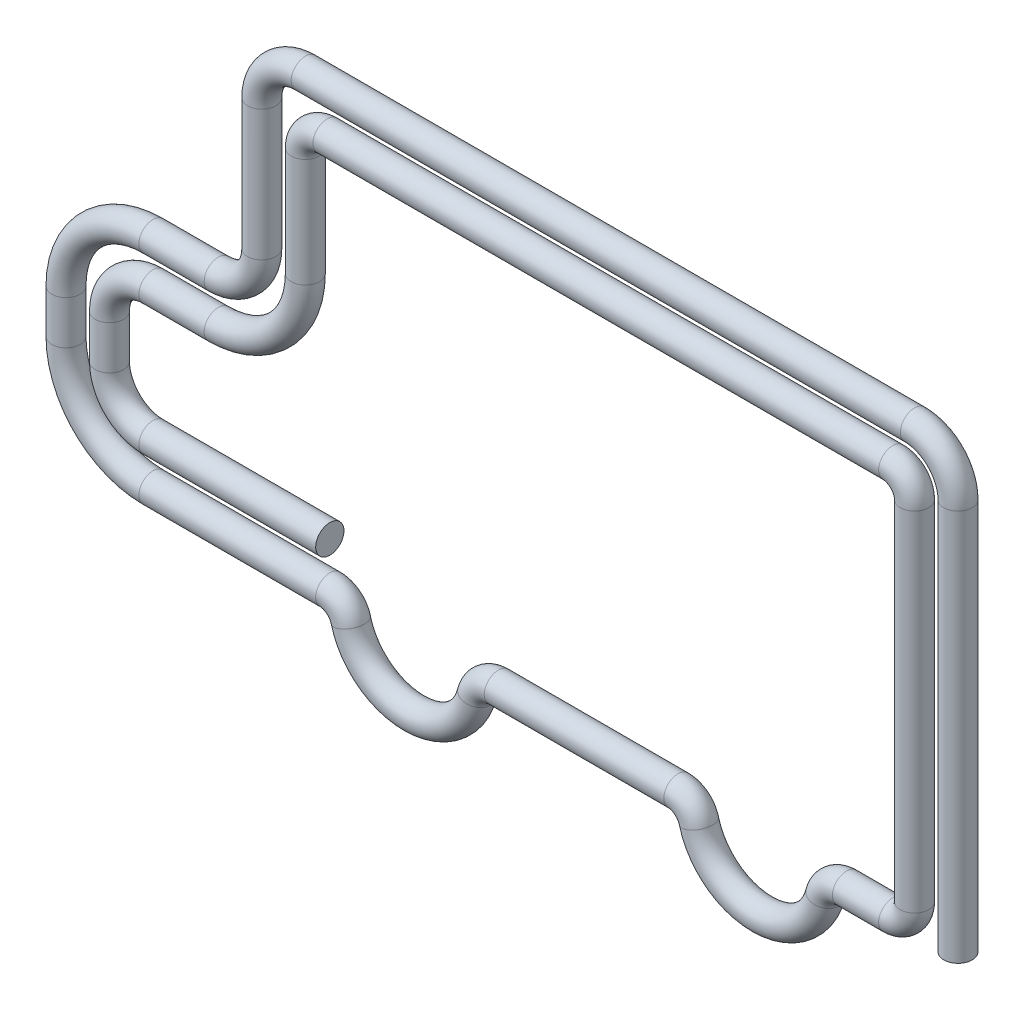
SolidWorks part; units mm, degrees
ref_plane "Спереди" through (0, 0, 0) normal (0, 0, 1) x (1, 0, 0)
ref_plane "Сверху" through (0, 0, 0) normal (0, 1, 0) x (1, 0, 0)
ref_plane "Справа" through (0, 0, 0) normal (1, 0, 0) x (0, 0, -1)
sketch "Эскиз1" plane through (0, 0, 0) normal (0, 0, 1) x (1, 0, 0)
  line L0 (0, 0) -> (0, 10) construction
  line L1 (-15, -10) -> (15, -10) construction
  line L2 (-15, -10) -> (-15, 10) construction
  line L3 (-15, 10) -> (15, 10) construction
  line L4 (15, -10) -> (15, 10) construction
  line L5 (-15, -10) -> (15, 10) construction
  line L6 (-15, 10) -> (15, -10) construction
  line L7 (-15, 8) -> (15, 8) construction
  line L8 (-15, -10) -> (-24, -10) construction
  line L9 (-15, -10) -> (-15, 0) construction
  line L10 (-15, 0) -> (-24, 0) construction
  line L11 (-24, -10) -> (-24, 0) construction
  circle A0 centre (-8, -10) radius 3 construction
  circle A1 centre (8, -10) radius 3 construction
  point P0 (0, 0)
  dimension "D3" = 6
  dimension "D4" = 8
  dimension "D1" = 30
  dimension "D2" = 20
  dimension "D5" = 9
  dimension "D6" = 10
  dimension "D7" = 2
sketch "Эскиз2" plane through (0, 0, 0) normal (0, 0, 1) x (1, 0, 0)
  line L0 (15, 10) -> (-13, 10)
  line L1 (-15, 8) -> (-15, 2)
  line L2 (-15, -10) -> (-15, 10) construction
  line L3 (-17, 0) -> (-20, 0)
  line L4 (-24, -4) -> (-24, -6)
  line L5 (-20, -10) -> (-11.873, -10)
  line L6 (-15, -10) -> (15, -10) construction
  line L7 (-4.127, -10) -> (4.127, -10)
  line L8 (11.873, -10) -> (14, -10)
  line L9 (15, -9) -> (15, 7)
  line L10 (14, 8) -> (-12, 8)
  line L12 (-24, -10) -> (-24, 0) construction
  line L13 (-13, 7) -> (-13, 2)
  line L14 (17, 8) -> (17, -10)
  line L15 (-17, -2) -> (-20, -2)
  line L16 (-22, -4) -> (-22, -6)
  line L17 (-20, -8) -> (-11.873, -8)
  line L18 (-13, 8) -> (-13, 2) construction
  circle A0 centre (-8, -10) radius 3 construction
  arc A1 (-10.9047, -10.75) -> (-5.0953, -10.75) centre (-8, -10) ccw
  arc A2 (5.0953, -10.75) -> (10.9047, -10.75) centre (8, -10) ccw
  circle A3 centre (8, -10) radius 3 construction
  arc A4 (-20, 0) -> (-24, -4) centre (-20, -4) ccw
  arc A5 (-24, -6) -> (-20, -10) centre (-20, -6) ccw
  arc A6 (-13, 10) -> (-15, 8) centre (-13, 8) ccw
  arc A7 (-15, 2) -> (-17, 0) centre (-17, 2) cw
  arc A8 (15, 10) -> (17, 8) centre (15, 8) cw
  arc A9 (-11.873, -10) -> (-10.9047, -10.75) centre (-11.873, -11) cw
  arc A10 (-5.0953, -10.75) -> (-4.127, -10) centre (-4.127, -11) cw
  arc A11 (4.127, -10) -> (5.0953, -10.75) centre (4.127, -11) cw
  arc A12 (10.9047, -10.75) -> (11.873, -10) centre (11.873, -11) cw
  arc A13 (14, -10) -> (15, -9) centre (14, -9) ccw
  arc A14 (15, 7) -> (14, 8) centre (14, 7) ccw
  arc A15 (-13, 2) -> (-17, -2) centre (-17, 2) cw
  arc A16 (-20, -2) -> (-22, -4) centre (-20, -4) ccw
  arc A17 (-22, -6) -> (-20, -8) centre (-20, -6) ccw
  arc A18 (-13, 7) -> (-12, 8) centre (-12, 7) cw
  point P2 (0, 0)
  point P38 (-24, -10)
  point P41 (-15, 10)
  point P44 (-15, 0)
  point P48 (-11, -10)
  point P51 (-5, -10)
  point P54 (5, -10)
  point P57 (11, -10)
  point P60 (15, -10)
  point P63 (15, 8)
  point P75 (0, 0)
  dimension "D3" = 4
  dimension "D4" = 2
  dimension "D5" = 2
  dimension "D6" = 1
  dimension "D2" = 1
  dimension "D1" = 2
  dimension "D7" = 2
ref_plane "Плоскость1" through (17, -10, 0) normal (0, -1, 0) x (-1, 0, 0)
sketch "Эскиз3" plane through (17, -10, 0) normal (0, -1, 0) x (-1, 0, 0)
  circle A0 centre (0, 0) radius 0.65
  dimension "D1" = 1.3
sweep "По траектории1" add profiles "Эскиз3" path "Эскиз2"
